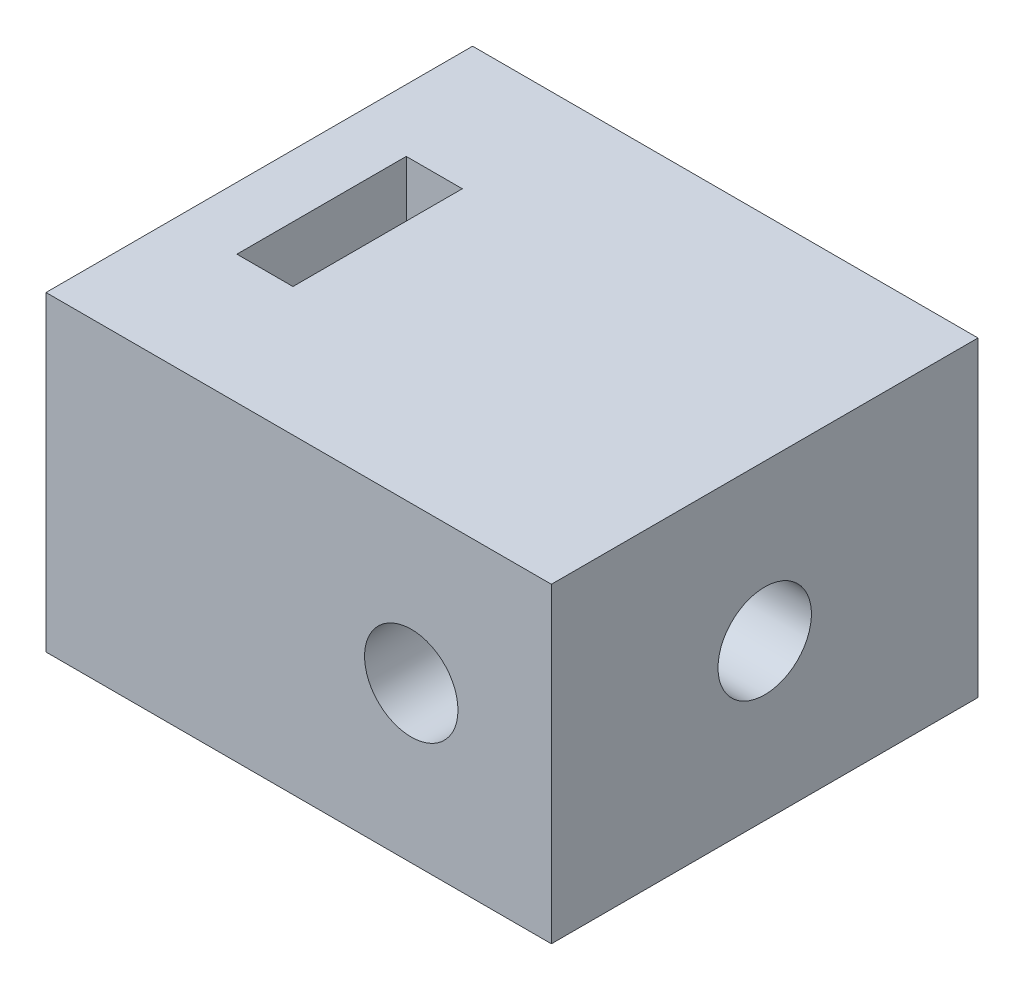
SolidWorks part; units mm, degrees
ref_plane "Front Plane" through (0, 0, 0) normal (0, 0, 1) x (1, 0, 0)
ref_plane "Top Plane" through (0, 0, 0) normal (0, 1, 0) x (1, 0, 0)
ref_plane "Right Plane" through (0, 0, 0) normal (1, 0, 0) x (0, 0, -1)
sketch "Sketch1" plane through (0, 0, 0) normal (0, 1, 0) x (1, 0, 0)
  line L1 (-8.205, 6.85) -> (8.205, 6.85)
  line L2 (-8.205, 6.85) -> (-8.205, -6.85)
  line L3 (-8.205, -6.85) -> (8.205, -6.85)
  line L4 (8.205, 6.85) -> (8.205, -6.85)
  line L5 (-8.205, 6.85) -> (8.205, -6.85) construction
  line L6 (-8.205, -6.85) -> (8.205, 6.85) construction
  point P0 (0, 0)
  dimension "D2" = 13.7
  dimension "D1" = 16.41
extrude "Boss-Extrude1" add sketch "Sketch1" along normal blind 10
sketch "Sketch2" plane through (0, 0, 6.85) normal (0, 0, 1) x (1, 0, 0)
  line L0 (5.205, 5) -> (8.205, 5) construction
  line L1 (8.205, 10) -> (8.205, 0) construction
  line L4 (5.0647, 2.645) -> (6.4243, 5)
  line L5 (6.4243, 5) -> (5.0647, 7.355)
  line L6 (5.0647, 7.355) -> (2.3453, 7.355)
  line L7 (2.3453, 7.355) -> (0.9857, 5)
  line L8 (0.9857, 5) -> (2.3453, 2.645)
  line L9 (2.3453, 2.645) -> (5.0647, 2.645)
  circle A0 centre (3.705, 5) radius 1.5
  circle A1 centre (6.2209, 6.6323) radius 0.0485 construction
  circle A2 centre (3.705, 5) radius 2.355 construction
  dimension "D1" = 3
  dimension "D2" = 3
  dimension "D3" = 4.71
extrude "Cut-Extrude1" cut sketch "Sketch2" against normal through all contours A0
ref_plane "Plane1" through (0, 5, 0) normal (0, -1, 0) x (-1, 0, 0)
sketch "Sketch3" plane through (-8.205, 0, 0) normal (-1, 0, 0) x (0, 0, 1)
  line L0 (0, 0) -> (0, 10) construction
  line L1 (-6.85, 10) -> (6.85, 10) construction
  circle A0 centre (0, 5) radius 1.5
  dimension "D1" = 3
extrude "Cut-Extrude2" cut sketch "Sketch3" against normal through all
sketch "Sketch5" plane through (0, 10, 0) normal (0, 1, 0) x (1, 0, 0)
  line L0 (-8.205, -6.85) -> (8.205, -6.85) construction
  line L1 (-8.205, 6.85) -> (-8.025, 6.85)
  line L2 (-8.205, 6.85) -> (-8.205, -6.85)
  line L3 (-8.205, -6.85) -> (-8.025, -6.85)
  line L4 (-8.025, 6.85) -> (-8.025, -6.85)
  dimension "D1" = 0.18
extrude "Cut-Extrude4" cut sketch "Sketch5" against normal through all
ref_plane "Plane2" through (-6.025, 0, 0) normal (-1, 0, 0) x (0, 0, 1)
sketch "Sketch4" plane through (-6.025, 0, 0) normal (-1, 0, 0) x (0, 0, 1)
  line L0 (0, 0) -> (0, 10) construction
  line L1 (0, 0) -> (0, 10) construction
  line L3 (2.7193, 5) -> (1.3597, 7.355)
  line L4 (1.3597, 7.355) -> (-1.3597, 7.355)
  line L5 (-1.3597, 7.355) -> (-2.7193, 5)
  line L6 (-2.7193, 5) -> (-1.3597, 2.645)
  line L7 (-1.3597, 2.645) -> (1.3597, 2.645)
  line L8 (1.3597, 2.645) -> (2.7193, 5)
  circle A0 centre (0, 5) radius 2.355 construction
  dimension "D1" = 4.71
extrude "Cut-Extrude3" cut sketch "Sketch4" against normal blind 1.8
sketch "Sketch6" plane through (0, 10, 0) normal (0, 1, 0) x (1, 0, 0)
  line L0 (-6.025, 2.7193) -> (-6.025, -2.7193)
  line L1 (-6.025, -2.7193) -> (-4.225, -2.7193)
  line L2 (-4.225, -2.7193) -> (-4.225, 2.7193)
  line L3 (-4.225, 2.7193) -> (-6.025, 2.7193)
  point P0 (-6.025, 2.7193)
  point P2 (-6.025, -2.7193)
  dimension "D1" = 1.8
extrude "Cut-Extrude5" cut sketch "Sketch6" against normal up to vertex (5 mm away) up to point (-6.025, 5, -2.7193)
equation "\"supportThickness\"=1.5"
equation "\"pcbThickness\"= 1.6"
equation "\"sideWallThickness\"= 1.5"
equation "\"bottomWallThickness\"= 6.0"
equation "\"topWallThickness\"= 2.0"
equation "\"wallTolerance\"= 0.2"
equation "\"totalHeight\"= 220.50 + \"wallTolerance\""
equation "\"totalWidth\"= 12 * \"motorDiameter\" + 11 * \"motor2motorHorizontal\" + 2 * \"wallTolerance\""
equation "\"totalDepth\"= 4 * \"motorDiameter\" + 2 * \"pcbThickness\" + 1 * \"motor2motorHorizontal\" + 4 * 0.10 + 2 * \"wallTolerance\""
equation "\"pinHeight\"= 115"
equation "\"pinWidth\"= 4.85"
equation "\"electricalComponents\"=53.04"
equation "\"motorDiameter\"=6.0"
equation "\"res\"= 2.0"
equation "\"pcbWidth\"= 106.67"
equation "\"supportDistance\"= 10.0"
equation "\"pcbLength\"= 216.23"
equation "\"motorSmallDiameter\"= 3.5"
equation "\"motorSmallLength\"= 0.4"
equation "\"motorShaftDiameter\"= 2.0"
equation "\"motorShaftLength\"= 2.7"
equation "\"motorShaftFlatDist\"= 1.5"
equation "\"motorWireDiameter\"= 0.5"
equation "\"motorWireDistance\"= 3.20"
equation "\"encoderLength\"= 3.2"
equation "\"encoderWidth\"= 1.7"
equation "\"encoderDepth\"=1.1"
equation "\"encoderTolerance\"=0.15"
equation "\"encoderDistance\"=1.0"
equation "\"pcbToWall\"= \"motorDiameter\" + \"wallTolerance\""
equation "\"pcbToPcb\"= 2 * \"motorDiameter\" + \"wallTolerance\" + 1.0"
equation "\"bracketBlockWidth\"= 13.20"
equation "\"topBlockLength\"=16.41"
equation "\"D1@Sketch1\"=\"topBlockLength\""
equation "\"bracketBlockHeight\"= 10.0"
equation "\"D1@Boss-Extrude1\"=\"bracketBlockHeight\""
equation "\"pcbExtension\"= 26.0"
equation "\"acrylicSideWallThickness\"= 2.0"
equation "\"smallBlockLength\"= 14"
equation "\"bottomBlockLength\"= 24"
equation "\"encoderToSwitchDistance\"= 7.35"
equation "\"encoderTicksSpacing\"= 0.65"
equation "\"motor2motorHorizontal\"= 1.0"
equation "\"motor2motorVertical\"= 1.80"
equation "\"length\"= 152.0"
